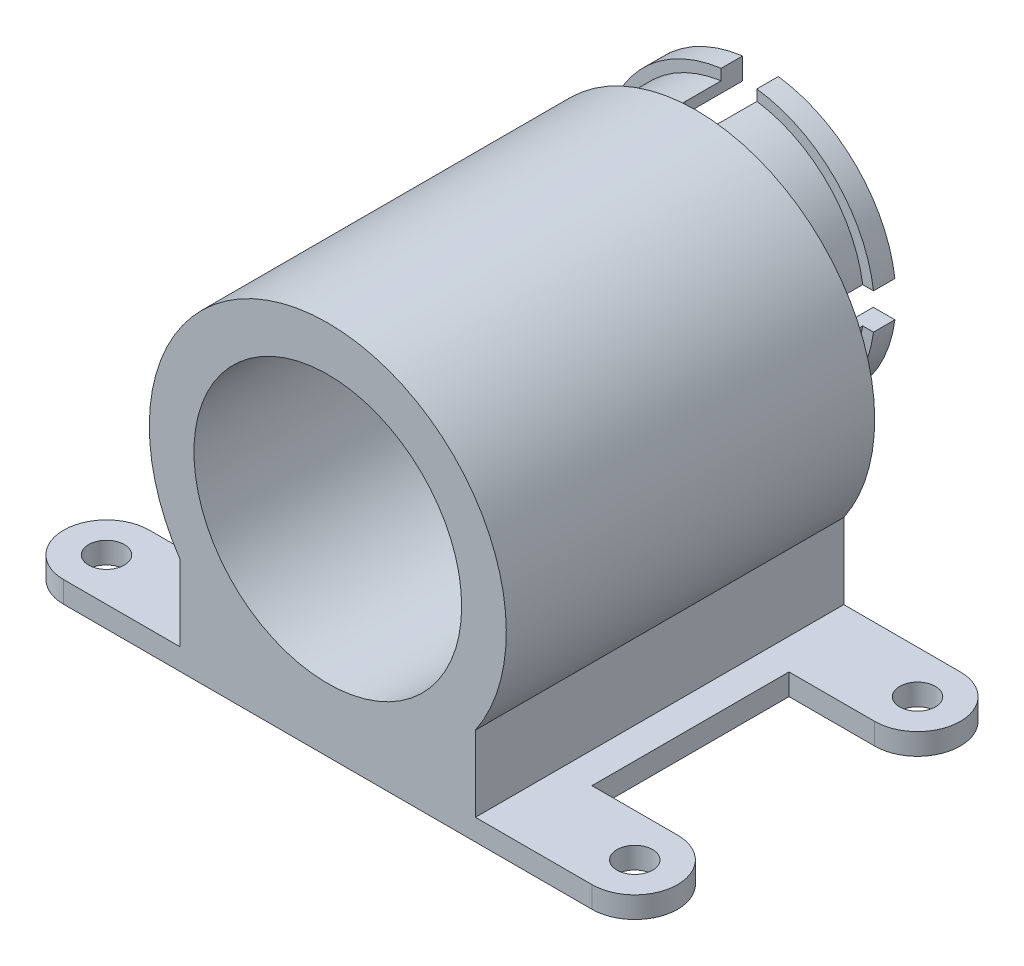
SolidWorks part; units mm, degrees
ref_plane "Alzado" through (0, 0, 0) normal (0, 0, 1) x (1, 0, 0)
ref_plane "Planta" through (0, 0, 0) normal (0, 1, 0) x (1, 0, 0)
ref_plane "Vista lateral" through (0, 0, 0) normal (1, 0, 0) x (0, 0, -1)
sketch "Croquis1" plane through (0, 0, 0) normal (0, 0, 1) x (1, 0, 0)
  circle A1 centre (0, 0) radius 21.1
  dimension "D2" = 42.2
extrude "Saliente-Extruir1" add sketch "Croquis1" along normal blind 51.6
sketch "Croquis2" plane through (0, 0, 51.6) normal (0, 0, 1) x (1, 0, 0)
  circle A0 centre (0, 0) radius 18.75
  dimension "D1" = 37.5
extrude "Cortar-Extruir1" cut sketch "Croquis2" against normal blind 48.6
sketch "Croquis3" plane through (0, 0, 0) normal (0, 0, -1) x (-1, 0, 0)
  circle A1 centre (0, 0) radius 21.1 construction
  circle A2 centre (0, 0) radius 21.1
sketch "Croquis5" plane through (0, 0, 3) normal (0, 0, 1) x (1, 0, 0)
  line L0 (0, -18.75) -> (0, 7) construction
  line L1 (0, 7) -> (0, 18.75) construction
  circle A0 centre (0, 0) radius 18.75
  circle A1 centre (0, 7) radius 6.275
  circle A3 centre (0, 7) radius 7.775
  dimension "D1" = 25.75
  dimension "D2" = 12.55
  dimension "D3" = 15.55
extrude "Saliente-Extruir3" add sketch "Croquis5" against normal blind 6 contours A3 A1
sketch "Croquis6" plane through (0, 0, 0) normal (0, 0, -1) x (-1, 0, 0)
  circle A0 centre (0, 7) radius 6.275
extrude "Cortar-Extruir2" cut sketch "Croquis6" against normal blind 66
sketch "Croquis8" plane through (0, 0, 0) normal (0, 0, -1) x (-1, 0, 0)
  circle A1 centre (0, 0) radius 21.1 construction
  circle A2 centre (0, 0) radius 21.1
sketch "Croquis9" plane through (0, 0, 0) normal (0, 0, -1) x (-1, 0, 0)
sketch "Croquis10" plane through (0, 0, 0) normal (0, 0, -1) x (-1, 0, 0)
  circle A0 centre (0, 0) radius 21.1
  circle A1 centre (0, 0) radius 25
  dimension "D1" = 50
extrude "Saliente-Extruir4" add sketch "Croquis10" against normal up to surface (51.6 mm away) up to face at (18.75, 0, 51.6)
sketch "Croquis11" plane through (0, 0, 0) normal (0, 0, -1) x (-1, 0, 0)
  circle A0 centre (0, 7) radius 16
  circle A1 centre (0, 7) radius 17.5
  dimension "D1" = 32
  dimension "D3" = 35
extrude "Saliente-Extruir5" add sketch "Croquis11" along normal blind 9
sketch "Croquis12" plane through (0, 0, -9) normal (0, 0, -1) x (-1, 0, 0)
  circle A0 centre (0, 7) radius 19
  circle A3 centre (0, 7) radius 17.5 construction
  circle A4 centre (0, 7) radius 17.5
  dimension "D1" = 38
extrude "Saliente-Extruir6" add sketch "Croquis12" against normal blind 3
sketch "Croquis13" plane through (0, 0, 0) normal (0, 0, -1) x (-1, 0, 0)
  line L0 (0, -25) -> (-25, -25)
  line L1 (-25, -25) -> (-25, -27.6328)
  line L2 (-25, -27.6328) -> (25, -27.6328)
  line L3 (25, -27.6328) -> (25, -25)
  line L4 (25, -25) -> (0, -25)
  line L5 (-20.6738, -14.0568) -> (20.6738, -14.0568)
  line L6 (-20.6738, -14.0568) -> (-20.6738, -25)
  line L7 (20.6738, -14.0568) -> (20.6738, -25)
  circle A1 centre (0, 0) radius 25 construction
  circle A2 centre (0, 0) radius 25
  circle M3 centre (0, 0) radius 25
extrude "Saliente-Extruir7" add sketch "Croquis13" against normal up to surface (51.6 mm away) contours L6 L0 M3 | L7 L4 M3 | L3 L4 L0 L1 L2 up to face at (18.75, 0, 51.6)
sketch "Croquis14" plane through (25, 0, 0) normal (1, 0, 0) x (0, 0, -1)
  line L0 (-51.6, -27.6328) -> (-51.6, -24.6328)
  line L5 (-51.6, -14.0568) -> (-51.6, -25) construction
  line L6 (-51.6, -24.6328) -> (0, -24.6328)
  line L7 (0, -14.0568) -> (0, -25) construction
  line L8 (0, -24.6328) -> (0, -27.6328)
  line L9 (0, -27.6328) -> (-51.6, -27.6328)
  dimension "D1" = 3
extrude "Saliente-Extruir8" add sketch "Croquis14" against normal up to surface (50 mm away) up to face at (-25, -26.3164, 25.8)
sketch "Croquis16" plane through (25, 0, 0) normal (1, 0, 0) x (0, 0, -1)
  line L0 (-51.6, -27.6328) -> (0, -27.6328) construction
  line L1 (-51.6, -24.6328) -> (-39.6, -24.6328)
  line L2 (-51.6, -24.6328) -> (-51.6, -27.6328)
  line L3 (-51.6, -27.6328) -> (-39.6, -27.6328)
  line L4 (-39.6, -24.6328) -> (-39.6, -27.6328)
  line L5 (0, -24.6328) -> (-51.6, -24.6328) construction
  line L6 (0, -27.6328) -> (-12, -27.6328)
  line L7 (0, -27.6328) -> (0, -24.6328)
  line L8 (0, -24.6328) -> (-12, -24.6328)
  line L9 (-12, -27.6328) -> (-12, -24.6328)
  dimension "D1" = 12
  dimension "D2" = 12
extrude "Saliente-Extruir9" add sketch "Croquis16" along normal blind 12
sketch "Croquis18" plane through (0, -24.6328, 0) normal (0, 1, 0) x (1, 0, 0)
  line L0 (37, -39.6) -> (37, -51.6) construction
  line L1 (37, -39.6) -> (25, -39.6) construction
  line L2 (37, -39.6) -> (37, -51.6)
  line L3 (37, 0) -> (37, -12) construction
  circle A0 centre (37, -45.6) radius 6
  circle A1 centre (37, -6) radius 6
  line M4 (37, -51.6) -> (37, -39.6)
  line M8 (37, -12) -> (37, 0)
  dimension "D1" = 12
extrude "Saliente-Extruir11" add sketch "Croquis18" against normal up to surface (3 mm away) contours A1 M8 | A0 M4 up to face at (18.5, -27.6328, 25.8)
sketch "Croquis19" plane through (0, -24.6328, 0) normal (0, 1, 0) x (1, 0, 0)
  line L0 (43, -45.6) -> (37, -45.6) construction
  line L1 (43, -6) -> (37, -6) construction
  arc A0 (37, -51.6) -> (37, -39.6) centre (37, -45.6) ccw construction
  arc A1 (37, -12) -> (37, 0) centre (37, -6) ccw construction
  circle A2 centre (37, -6) radius 2.5
  circle A3 centre (37, -45.6) radius 2.5
  dimension "D1" = 5
  dimension "D2" = 5
extrude "Cortar-Extruir5" cut sketch "Croquis19" against normal blind 15
sketch "Croquis20" plane through (-25, 0, 0) normal (-1, 0, 0) x (0, 0, 1)
  line L0 (51.6, -27.6328) -> (0, -27.6328) construction
  line L1 (0, -24.6328) -> (12, -24.6328)
  line L2 (0, -24.6328) -> (0, -27.6328)
  line L3 (0, -27.6328) -> (12, -27.6328)
  line L4 (12, -24.6328) -> (12, -27.6328)
  line L5 (0, -24.6328) -> (51.6, -24.6328) construction
  line L6 (51.6, -27.6328) -> (39.6, -27.6328)
  line L7 (51.6, -27.6328) -> (51.6, -24.6328)
  line L8 (51.6, -24.6328) -> (39.6, -24.6328)
  line L9 (39.6, -27.6328) -> (39.6, -24.6328)
  dimension "D1" = 12
  dimension "D2" = 12
extrude "Saliente-Extruir12" add sketch "Croquis20" along normal blind 12
sketch "Croquis21" plane through (0, -24.6328, 0) normal (0, 1, 0) x (1, 0, 0)
  line L0 (-37, -12) -> (-37, 0) construction
  line L1 (-37, -51.6) -> (-37, -39.6) construction
  line L2 (-37, 0) -> (-37, -12)
  line L3 (-37, -39.6) -> (-37, -51.6)
  circle A0 centre (-37, -6) radius 6
  circle A1 centre (-37, -45.6) radius 6
  line M3 (-37, 0) -> (-37, -12)
  line M7 (-37, -39.6) -> (-37, -51.6)
  dimension "D1" = 12
  dimension "D2" = 12
extrude "Saliente-Extruir13" add sketch "Croquis21" against normal up to surface (3 mm away) contours A0 M3 | A1 M7 up to face at (37, -27.6328, 3.5)
sketch "Croquis22" plane through (0, -24.6328, 0) normal (0, 1, 0) x (1, 0, 0)
  line L0 (-43, -6) -> (-37, -6) construction
  line L1 (-43, -45.6) -> (-37, -45.6) construction
  arc A0 (-37, 0) -> (-37, -12) centre (-37, -6) ccw construction
  arc A1 (-37, -39.6) -> (-37, -51.6) centre (-37, -45.6) ccw construction
  circle A2 centre (-37, -6) radius 2.5
  circle A3 centre (-37, -45.6) radius 2.5
  dimension "D1" = 5
  dimension "D2" = 5
extrude "Cortar-Extruir6" cut sketch "Croquis22" against normal blind 12
sketch "Croquis23" plane through (0, 0, -9) normal (0, 0, -1) x (-1, 0, 0)
  line L0 (0, 7) -> (0, 23)
  line L1 (0, 7) -> (-19, 7)
  line L2 (0, 23) -> (0, 26)
  line L3 (-19, 7) -> (-19, 9.5)
  line L4 (-19, 9.5) -> (-23.3765, 9.5)
  line L5 (-23.3765, 9.5) -> (-23.3765, 4.5)
  line L6 (-19, 7) -> (-19, 4.5)
  line L7 (-23.3765, 4.5) -> (-19, 4.5)
  line L8 (0, 26) -> (-2.5, 26)
  line L9 (0, 26) -> (2.5, 26)
  line L10 (-2.5, 26) -> (-2.5, 29.2828)
  line L11 (-2.5, 29.2828) -> (2.5, 29.2828)
  line L12 (2.5, 29.2828) -> (2.5, 26)
  circle A0 centre (0, 7) radius 16 construction
  circle A1 centre (0, 7) radius 19 construction
  dimension "D1" = 2.5
  dimension "D2" = 2.5
  dimension "D3" = 2.5
  dimension "D4" = 2.5
extrude "Saliente-Extruir14" add sketch "Croquis23" against normal blind 8 separate body contours L12 L11 L10 L8 L9 | L5 L7 L6 L3 L4
sketch "Croquis24" plane through (0, 0, -9) normal (0, 0, -1) x (-1, 0, 0)
  line L0 (-23.3765, 4.5) -> (-19, 4.5) construction
  line L1 (-23.3765, 9.5) -> (-19, 9.5)
  line L2 (-23.3765, 9.5) -> (-23.3765, 4.5)
  line L3 (-23.3765, 4.5) -> (-19, 4.5)
  line L4 (-19, 9.5) -> (-19, 4.5)
  line L6 (-2.5, 29.2828) -> (2.5, 29.2828)
  line L7 (-2.5, 29.2828) -> (-2.5, 26)
  line L8 (-2.5, 26) -> (2.5, 26)
  line L9 (2.5, 29.2828) -> (2.5, 26)
sketch "Croquis26" plane through (0, 29.2828, 0) normal (0, 1, 0) x (1, 0, 0)
  line L0 (0, 1) -> (0, 9) construction
  line L2 (2.5, 1) -> (-2.5, 1) construction
  line L3 (-2.5, 1) -> (-2.5, 9)
  line L4 (2.5, 1) -> (2.5, 9)
  line L5 (2.5, 9) -> (-2.5, 9) construction
  line L7 (-2.2913, 0) -> (2.2913, 0)
  line L8 (21.1, 0) -> (-21.1, 0) construction
  arc A0 (-2.5, 1) -> (2.5, 1) centre (0, 1) ccw
  arc A1 (2.5, 9) -> (-2.5, 9) centre (0, 9) ccw
  point P4 (0, 5)
  line M2 (2.5, 9) -> (-2.5, 9)
  line M3 (-2.5, 9) -> (-2.5, 1)
  line M4 (-2.5, 1) -> (2.5, 1)
  line M5 (2.5, 1) -> (2.5, 9)
  dimension "D1" = 0
  dimension "D2" = 2.5
extrude "Cortar-Extruir11" cut sketch "Croquis26" against normal blind 10 contours A1 M2 | L0 M4 M2 M3 | L0 M4 M5 M2 | L7 A0 M4
sketch "Croquis27" plane through (23.3765, 0, 0) normal (1, 0, 0) x (0, 0, -1)
  line L0 (9, 7) -> (1, 7) construction
  line L1 (9, 9.5) -> (9, 4.5) construction
  line L2 (1, 9.5) -> (1, 4.5) construction
  line L3 (9, 4.5) -> (1, 4.5)
  line L4 (9, 9.5) -> (1, 9.5)
  line L5 (0, 9.2913) -> (0, 4.7087)
  line L6 (0, -21.1) -> (0, 21.1) construction
  arc A0 (9, 4.5) -> (9, 9.5) centre (9, 7) ccw
  arc A1 (1, 9.5) -> (1, 4.5) centre (1, 7) ccw
  point P6 (5, 7)
  line M1 (9, 4.5) -> (9, 9.5)
  line M2 (9, 9.5) -> (1, 9.5)
  line M3 (1, 9.5) -> (1, 4.5)
  line M4 (1, 4.5) -> (9, 4.5)
  dimension "D1" = 2.5
extrude "Cortar-Extruir12" cut sketch "Croquis27" against normal blind 13 contours A1 L5 M3 | L0 M1 M2 M3 | L0 M1 M3 M4 | A0 M1
